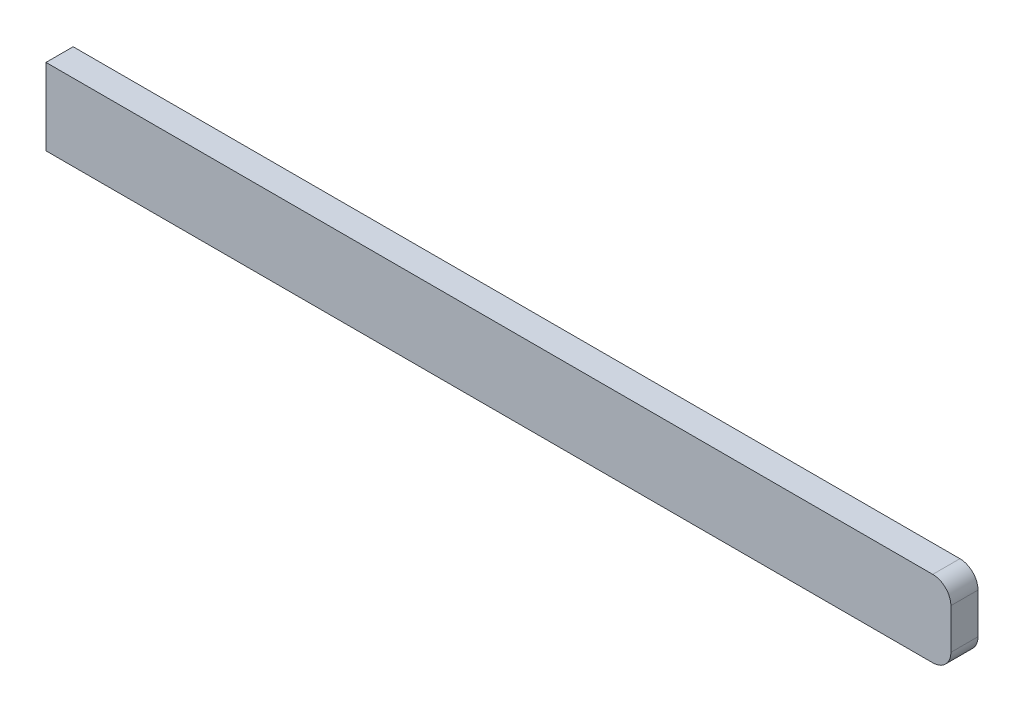
SolidWorks part; units mm, degrees
ref_plane "Alzado" through (0, 0, 0) normal (0, 0, 1) x (1, 0, 0)
ref_plane "Planta" through (0, 0, 0) normal (0, 1, 0) x (1, 0, 0)
ref_plane "Vista lateral" through (0, 0, 0) normal (1, 0, 0) x (0, 0, -1)
sketch "Sketch1" plane through (0, 0, 0) normal (0, 0, 1) x (1, 0, 0)
  line L0 (-12.7, 304.8) -> (-12.7, 0) construction
  line L1 (-12.7, 77.7) -> (137.3, 77.7)
  line L2 (-12.7, 77.7) -> (-12.7, 65)
  line L3 (-12.7, 65) -> (137.3, 65)
  line L4 (137.3, 77.7) -> (137.3, 65)
  circle A0 centre (110, 65) radius 25.4 construction
  dimension "D1" = 12.7
  dimension "D2" = 150
  dimension "D3" = 12.7
extrude "Boss-Extrude1" add sketch "Sketch1" along normal blind 4.5
fillet "Fillet1" radius 3 2 edges at (137.3, 65, 2.25) (137.3, 77.7, 2.25)
